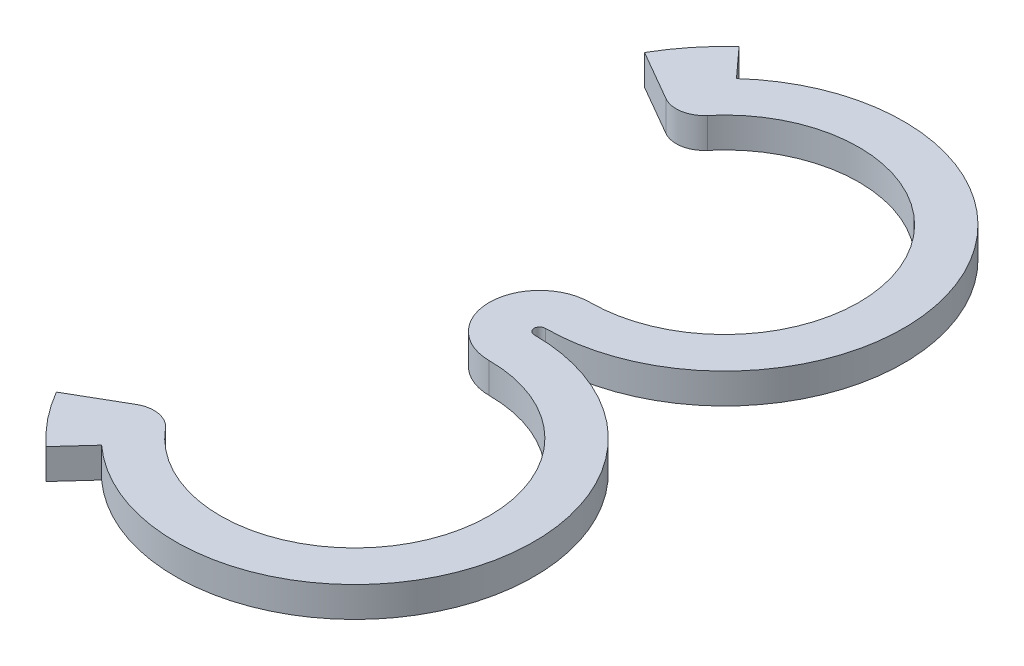
SolidWorks part; units mm, degrees
ref_plane "前视基准面" through (0, 0, 0) normal (0, 0, 1) x (1, 0, 0)
ref_plane "上视基准面" through (0, 0, 0) normal (0, 1, 0) x (1, 0, 0)
ref_plane "右视基准面" through (0, 0, 0) normal (1, 0, 0) x (0, 0, -1)
sketch "草图1" plane through (0, 0, 0) normal (0, 1, 0) x (1, 0, 0)
  line L0 (0, 0) -> (0, -33) construction
  line L1 (-12.3693, 7.1414) -> (-16.8875, 9.75)
  line L2 (0, 0) -> (0, 16) construction
  line L3 (-12.3693, 7.1414) -> (0, 0) construction
  line L4 (0, 0) -> (-8.0762, 8.8755) construction
  line L5 (-10.7682, 11.8341) -> (-13.1238, 14.4228)
  line L6 (0, -16.5) -> (33.8578, -16.5) construction
  line L7 (0, -33) -> (-8.0762, -41.8755) construction
  line L8 (-12.3693, -40.1414) -> (0, -33) construction
  line L9 (0, -33) -> (0, -49) construction
  line L10 (-10.7682, -44.8341) -> (-13.1238, -47.4228)
  line L11 (-12.3693, -40.1414) -> (-16.8875, -42.75)
  arc A0 (0, -12) -> (-9.2022, 7.7019) centre (0, 0) ccw
  circle A1 centre (0, -33) radius 12 construction
  arc A2 (0, -16) -> (-10.7682, 11.8341) centre (0, 0) ccw
  arc A3 (-4.362, -17.6061) -> (0, -17) centre (0, -33) ccw construction
  arc A4 (0, -12) -> (0, -21) centre (0, -16.5) ccw
  arc A6 (-9.2022, 7.7019) -> (-12.3693, 7.1414) centre (-11.1193, 9.3065) cw
  arc A7 (-16.8875, 9.75) -> (-13.1238, 14.4228) centre (0, 0) cw
  arc A8 (-16.8875, -42.75) -> (-13.1238, -47.4228) centre (0, -33) ccw
  arc A9 (-9.2022, -40.7019) -> (-12.3693, -40.1414) centre (-11.1193, -42.3065) ccw
  arc A10 (0, -17) -> (-10.7682, -44.8341) centre (0, -33) cw
  arc A11 (0, -21) -> (-9.2022, -40.7019) centre (0, -33) cw
  arc A12 (0, -16) -> (0, -17) centre (0, -16.5) ccw
  dimension "D1" = 24
  dimension "D2" = 32
  dimension "D3" = 9
  dimension "D5" = 2.5
  dimension "D6" = 19.5
  dimension "D7" = 6
  dimension "D4" = 60
extrude "凸台-拉伸1" add sketch "草图1" along normal blind 2.7
